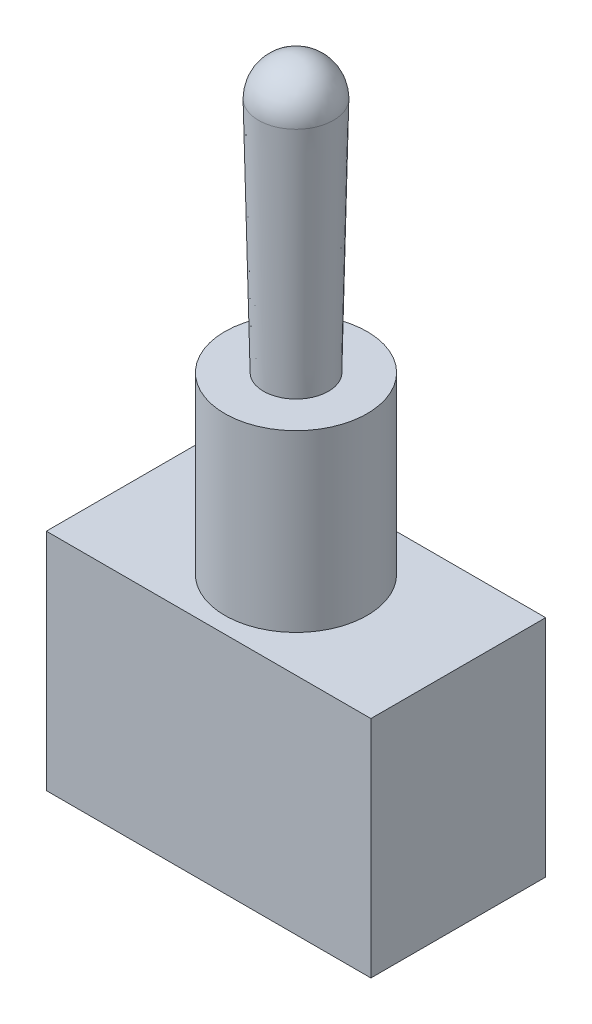
SolidWorks part; units mm, degrees
ref_plane "前视基准面" through (0, 0, 0) normal (0, 0, 1) x (1, 0, 0)
ref_plane "上视基准面" through (0, 0, 0) normal (0, 1, 0) x (1, 0, 0)
ref_plane "右视基准面" through (0, 0, 0) normal (1, 0, 0) x (0, 0, -1)
sketch "草图1" plane through (0, 0, 0) normal (0, 0, 1) x (1, 0, 0)
  line L1 (6.5, -4.5) -> (-6.5, -4.5)
  line L2 (6.5, -4.5) -> (6.5, 4.5)
  line L3 (6.5, 4.5) -> (-6.5, 4.5)
  line L4 (-6.5, -4.5) -> (-6.5, 4.5)
  line L5 (6.5, -4.5) -> (-6.5, 4.5) construction
  line L6 (6.5, 4.5) -> (-6.5, -4.5) construction
  point P0 (0, 0)
  dimension "D1" = 9
  dimension "D2" = 13
extrude "凸台-拉伸1" add sketch "草图1" along normal blind 7
sketch "草图2" plane through (0, 4.5, 0) normal (0, 1, 0) x (1, 0, 0)
  line L0 (6.5, -3.5) -> (5.1667, -3.5) construction
  line L1 (6.5, -7) -> (6.5, 0) construction
  circle A0 centre (0, -3.5) radius 2.85
  dimension "D1" = 5.7
extrude "凸台-拉伸2" add sketch "草图2" along normal blind 7
sketch "草图3" plane through (0, 0, 0) normal (1, 0, 0) x (0, 0, -1)
  line L0 (-3.5, 11.5) -> (-3.5, 21) construction
  line L1 (-0.65, 11.5) -> (-6.35, 11.5) construction
  line L2 (-3.5, 11.5) -> (-4.8, 11.5)
  line L3 (-4.8, 11.5) -> (-5, 21)
  line L4 (-3.5, 22.5) -> (-3.5, 11.5)
  arc A0 (-5, 21) -> (-3.5, 22.5) centre (-3.5, 21) cw
  dimension "D3" = 1.5
  dimension "D1" = 1.3
  dimension "D2" = 11
revolve "旋转1" add sketch "草图3" angle 360 about L0
